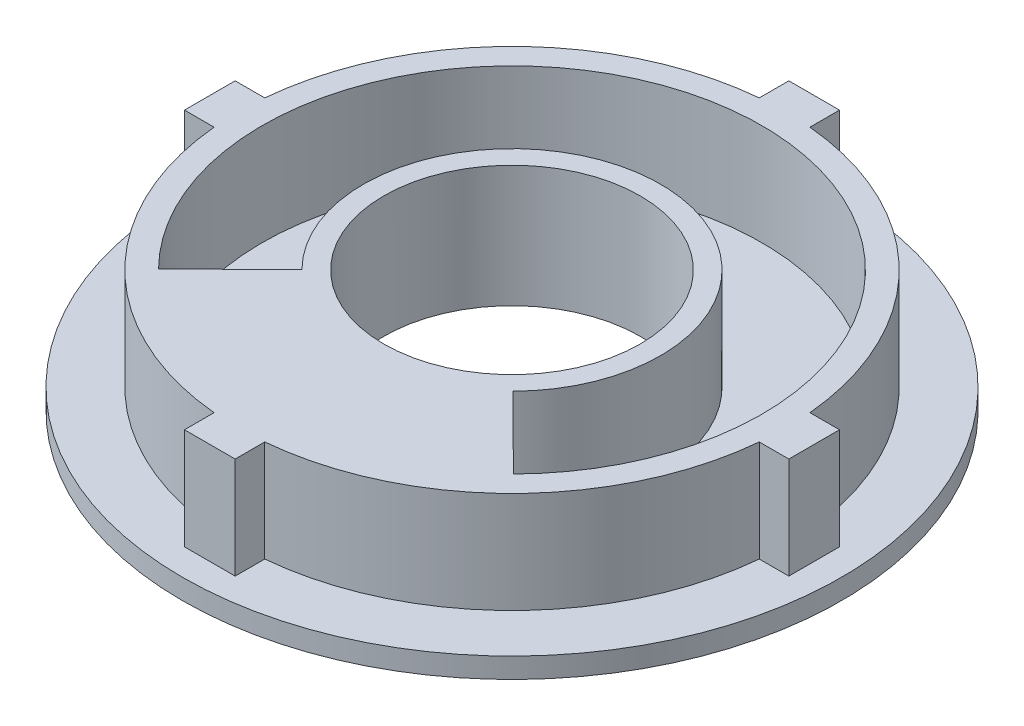
SolidWorks part; units mm, degrees
ref_plane "Front Plane" through (0, 0, 0) normal (0, 0, 1) x (1, 0, 0)
ref_plane "Top Plane" through (0, 0, 0) normal (0, 1, 0) x (1, 0, 0)
ref_plane "Right Plane" through (0, 0, 0) normal (1, 0, 0) x (0, 0, -1)
sketch "Sketch1" plane through (0, 0, 0) normal (0, 1, 0) x (1, 0, 0)
  line L0 (-17.5, -17.3601) -> (-10.4006, -10.3175)
  line L1 (0, -6.6) -> (0, 6.6) construction
  line L2 (17.5, -17.3601) -> (10.4006, -10.3175)
  line L4 (-17.5, -17.3601) -> (3.5272, -38.5567) construction
  circle A0 centre (0, 0) radius 27
  arc A1 (10.4006, -10.3175) -> (-10.4006, -10.3175) centre (0, 0) ccw
  arc A2 (17.5, -17.3601) -> (-17.5, -17.3601) centre (0, 0) ccw
  circle A3 centre (0, 0) radius 12.65
  arc A4 (16.047, 11.8457) -> (13.9503, -13.8388) centre (0.18, 0.2132) cw construction
  circle A5 centre (0, 0) radius 19.9533 construction
  dimension "D1" = 54
  dimension "D2" = 2.35
  dimension "D3" = 10
  dimension "D4" = 2
  dimension "D5" = 35
extrude "Boss-Extrude1" add sketch "Sketch1" along normal blind 10
sketch "Sketch2" plane through (0, 0, 0) normal (0, -1, 0) x (1, 0, 0)
  circle A0 centre (0, 0) radius 32.5
  circle A1 centre (0, 0) radius 12.65
  circle A2 centre (0, 0) radius 12.65 construction
  point P6 (45.0118, -20.1582)
  dimension "D1" = 65
extrude "Boss-Extrude2" add sketch "Sketch2" along normal blind 2
sketch "Sketch3" plane through (0, 0, 0) normal (0, 1, 0) x (1, 0, 0)
  line L0 (0, -6.6) -> (0, 6.6) construction
  line L1 (-2.5, 29.8) -> (2.5, 29.8)
  line L2 (-2.5, 29.8) -> (-2.5, 25.4032)
  line L3 (-2.5, 25.4032) -> (2.5, 25.4032)
  line L4 (2.5, 29.8) -> (2.5, 25.4032)
  line L5 (-2.5, 29.8) -> (2.5, 25.4032) construction
  line L6 (-2.5, 25.4032) -> (2.5, 29.8) construction
  line L7 (29.8, 2.5) -> (25.4032, 2.5)
  line L8 (29.8, 2.5) -> (29.8, -2.5)
  line L9 (29.8, -2.5) -> (25.4032, -2.5)
  line L10 (25.4032, 2.5) -> (25.4032, -2.5)
  line L11 (2.5, -29.8) -> (2.5, -25.4032)
  line L12 (2.5, -29.8) -> (-2.5, -29.8)
  line L13 (-2.5, -29.8) -> (-2.5, -25.4032)
  line L14 (2.5, -25.4032) -> (-2.5, -25.4032)
  line L15 (-29.8, -2.5) -> (-25.4032, -2.5)
  line L16 (-29.8, -2.5) -> (-29.8, 2.5)
  line L17 (-29.8, 2.5) -> (-25.4032, 2.5)
  line L18 (-25.4032, -2.5) -> (-25.4032, 2.5)
  circle A1 centre (0, 0) radius 27 construction
  point P0 (0, 27.6016)
  dimension "D2" = 29.8
  dimension "D1" = 5
  dimension "D3" = 4
extrude "Boss-Extrude3" add sketch "Sketch3" along normal blind 10
